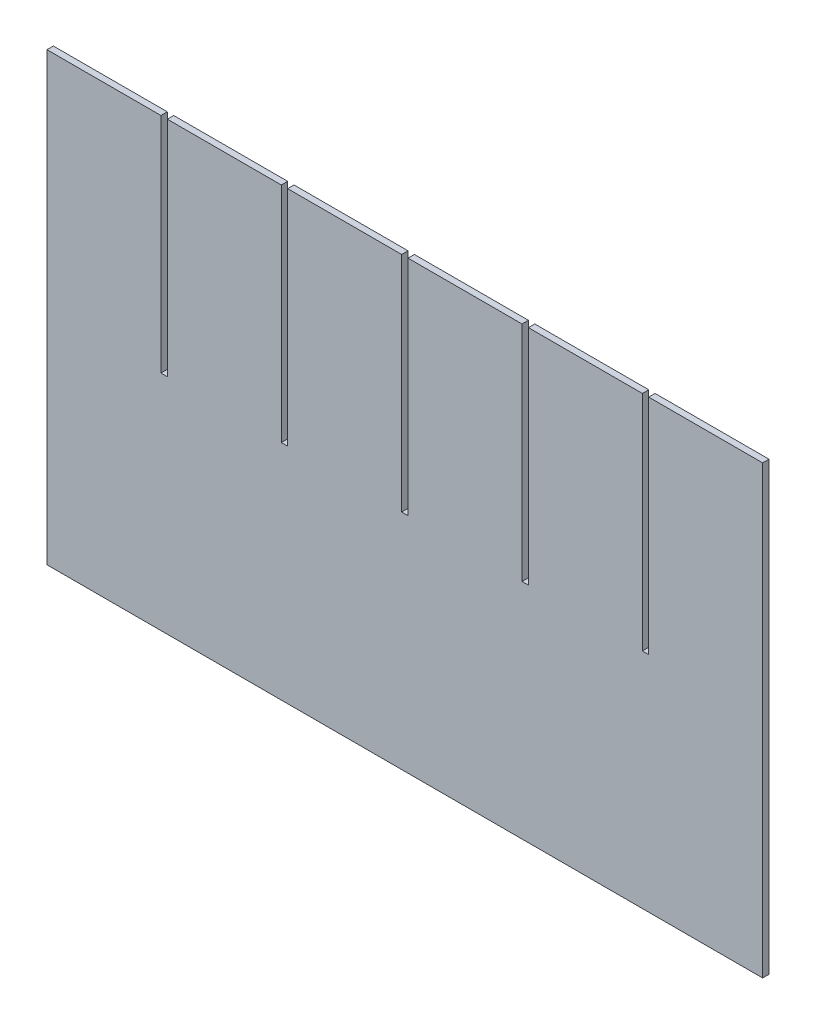
SolidWorks part; units mm, degrees
ref_plane "Front Plane" through (0, 0, 0) normal (0, 0, 1) x (1, 0, 0)
ref_plane "Top Plane" through (0, 0, 0) normal (0, 1, 0) x (1, 0, 0)
ref_plane "Right Plane" through (0, 0, 0) normal (1, 0, 0) x (0, 0, -1)
sketch "Sketch1" plane through (0, 0, 0) normal (0, 0, 1) x (1, 0, 0)
  line L1 (-112.3, -70) -> (112.3, -70)
  line L2 (-112.3, -70) -> (-112.3, 70)
  line L3 (-112.3, 70) -> (112.3, 70)
  line L4 (112.3, -70) -> (112.3, 70)
  line L5 (-112.3, -70) -> (112.3, 70) construction
  line L6 (-112.3, 70) -> (112.3, -70) construction
  point P0 (0, 0)
  dimension "D1" = 224.6
  dimension "D2" = 140
extrude "Boss-Extrude1" add sketch "Sketch1" along normal blind 2
sketch "Sketch2" plane through (0, 0, 2) normal (0, 0, 1) x (1, 0, 0)
  line L2 (112.3, 70) -> (-112.3, 70) construction
  line L3 (-76.53, 70) -> (-76.53, 0)
  line L4 (-76.53, 0) -> (-74.53, 0)
  line L6 (-74.53, 70) -> (-74.53, 0)
  line L9 (-38.76, 70) -> (-38.76, 0)
  line L10 (-38.76, 0) -> (-36.76, 0)
  line L11 (36.78, 70) -> (36.78, 0)
  line L13 (1.01, 70) -> (1.01, 0)
  line L14 (-0.99, 70) -> (-0.99, 0)
  line L16 (-36.76, 70) -> (-36.76, 0)
  line L17 (-0.99, 0) -> (1.01, 0)
  line L20 (76.55, 70) -> (76.55, 0)
  line L21 (74.55, 70) -> (74.55, 0)
  line L23 (38.78, 70) -> (38.78, 0)
  line L24 (36.78, 0) -> (38.78, 0)
  line L25 (74.55, 0) -> (76.55, 0)
  line L26 (-76.53, 70) -> (-74.53, 70)
  line L27 (-38.76, 70) -> (-36.76, 70)
  line L28 (-0.99, 70) -> (1.01, 70)
  line L29 (74.55, 70) -> (76.55, 70)
  line L30 (-76.53, 70) -> (-74.53, 70)
  line L31 (36.78, 70) -> (38.78, 70)
  line M29 (112.3, 70) -> (-112.3, 70)
  dimension "D3" = 70
extrude "Cut-Extrude3" cut sketch "Sketch2" against normal through all contours L6 L3 L4 M29 | L16 L9 L10 M29 | L14 L17 L13 M29 | L21 L25 L20 M29 | L11 L24 L23 M29
